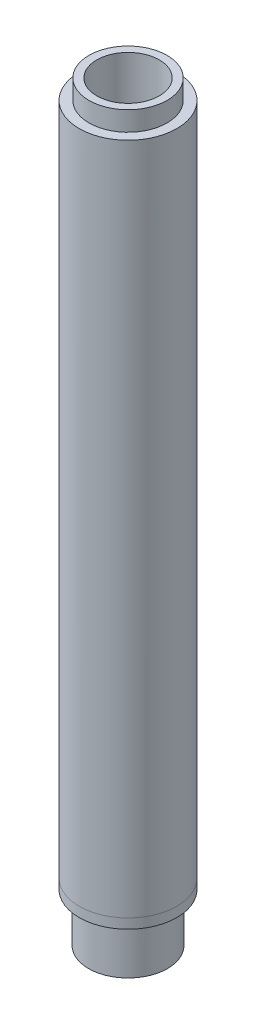
SolidWorks part; units mm, degrees
ref_plane "Front Plane" through (0, 0, 0) normal (0, 0, 1) x (1, 0, 0)
ref_plane "Top Plane" through (0, 0, 0) normal (0, 1, 0) x (1, 0, 0)
ref_plane "Right Plane" through (0, 0, 0) normal (1, 0, 0) x (0, 0, -1)
sketch "Sketch1" plane through (0, 0, 0) normal (0, 1, 0) x (1, 0, 0)
  circle A0 centre (0, 0) radius 12.7
  dimension "D1" = 25.4
extrude "Boss-Extrude1" add sketch "Sketch1" along normal blind 177.8
sketch "Sketch4" plane through (0, 177.8, 0) normal (0, 1, 0) x (1, 0, 0)
  circle A2 centre (0, 0) radius 10.16
  circle A3 centre (0, 0) radius 10.16
  dimension "D1" = 2.54
extrude "Boss-Extrude2" add sketch "Sketch4" along normal blind 5.08
sketch "Sketch5" plane through (0, 182.88, 0) normal (0, 1, 0) x (1, 0, 0)
  circle A0 centre (0, 0) radius 10.16 construction
  circle A1 centre (0, 0) radius 10.16 construction
  circle A2 centre (0, 0) radius 8.128
  dimension "D1" = 2.032
extrude "Cut-Extrude1" cut sketch "Sketch5" against normal through all
sketch "Sketch6" plane through (0, 0, 0) normal (0, -1, 0) x (1, 0, 0)
  circle A0 centre (0, 0) radius 10.287
  circle A1 centre (0, 0) radius 8.128 construction
  circle A2 centre (0, 0) radius 8.128
  dimension "D1" = 20.574
extrude "Boss-Extrude3" add sketch "Sketch6" along normal blind 12.7
sketch "Sketch7" plane through (0, -12.7, 0) normal (0, -1, 0) x (1, 0, 0)
  circle A0 centre (0, 0) radius 12.7 construction
  circle A1 centre (0, 0) radius 12.7
sketch "Sketch8" plane through (0, 182.88, 0) normal (0, 1, 0) x (1, 0, 0)
  circle A0 centre (0, 0) radius 12.7 construction
  circle A1 centre (0, 0) radius 12.7
ref_plane "Plane1" through (0, 2.54, 0) normal (0, -1, 0) x (-1, 0, 0)
split "Split1" trim tools "Plane1" bodies to split 104 resulting bodies 112 113
